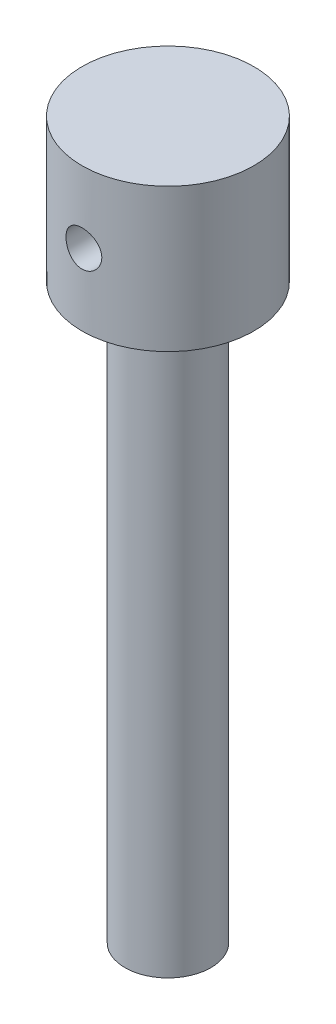
SolidWorks part; units mm, degrees
ref_plane "Front Plane" through (0, 0, 0) normal (0, 0, 1) x (1, 0, 0)
ref_plane "Top Plane" through (0, 0, 0) normal (0, 1, 0) x (1, 0, 0)
ref_plane "Right Plane" through (0, 0, 0) normal (1, 0, 0) x (0, 0, -1)
sketch "Sketch2" plane through (0, 0, 0) normal (0, 1, 0) x (1, 0, 0)
  circle A0 centre (0, 0) radius 12
  dimension "D1" = 24
extrude "Boss-Extrude1" add sketch "Sketch2" along normal blind 20
sketch "Sketch3" plane through (0, 0, 0) normal (0, -1, 0) x (1, 0, 0)
  circle A0 centre (0, 0) radius 6
  dimension "D1" = 12
extrude "Boss-Extrude2" add sketch "Sketch3" along normal blind 80
sketch "Sketch4" plane through (0, 0, 0) normal (0, 0, 1) x (1, 0, 0)
  line L0 (0, 20) -> (0, 0) construction
  line L1 (12, 20) -> (-12, 20) construction
  circle A0 centre (0, 10) radius 2.5
  dimension "D1" = 5
  dimension "D2" = 10
extrude "Cut-Extrude1" cut sketch "Sketch4" against normal through all both and the other way through all
